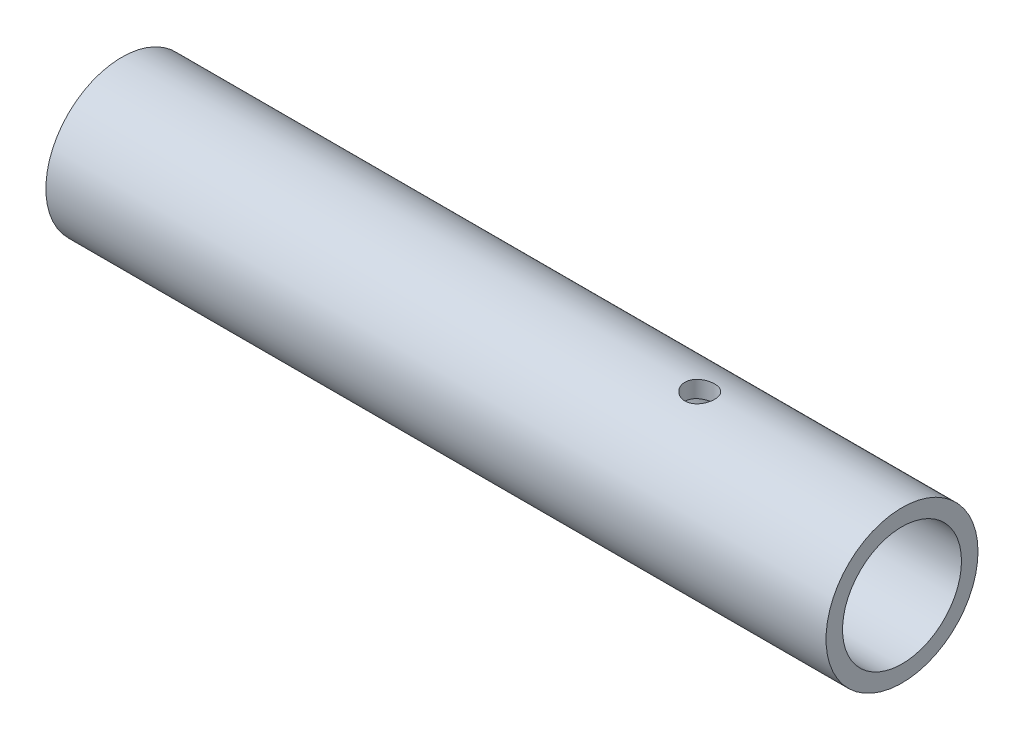
SolidWorks part; units mm, degrees
ref_plane "Front Plane" through (0, 0, 0) normal (0, 0, 1) x (1, 0, 0)
ref_plane "Top Plane" through (0, 0, 0) normal (0, 1, 0) x (1, 0, 0)
ref_plane "Right Plane" through (0, 0, 0) normal (1, 0, 0) x (0, 0, -1)
sketch "Sketch1" plane through (0, 0, 0) normal (1, 0, 0) x (0, 0, -1)
  circle A0 centre (0, 0) radius 16.7005
  circle A1 centre (0, 0) radius 13.0683
  dimension "D1" = 33.401
  dimension "D2" = 26.1366
extrude "Boss-Extrude1" add sketch "Sketch1" along normal blind 254
sketch "Sketch2" plane through (0, 0, 0) normal (0, 0, 1) x (1, 0, 0)
  line L0 (0, 0) -> (25.4, 0) construction
  line L1 (0, 16.7005) -> (0, -16.7005) construction
  line L2 (127, 16.7005) -> (127, -16.7005) construction
  line L3 (254, 16.7005) -> (0, 16.7005) construction
  line L4 (0, -16.7005) -> (254, -16.7005) construction
  line L5 (254, 0) -> (228.6, 0) construction
  circle A0 centre (25.4, 0) radius 3.2639
  circle A1 centre (228.6, 0) radius 3.2639
  dimension "D1" = 6.5278
  dimension "D2" = 25.4
extrude "Cut-Extrude1" [suppressed] cut sketch "Sketch2" against normal through all both and the other way through all
sketch "Sketch3" plane through (0, 0, 0) normal (0, 1, 0) x (1, 0, 0)
  line L0 (127, 16.7005) -> (127, -16.7005) construction
  line L1 (254, 16.7005) -> (0, 16.7005) construction
  line L2 (0, -16.7005) -> (254, -16.7005) construction
  circle A0 centre (127, 0) radius 3.2639
  dimension "D1" = 6.5278
extrude "Cut-Extrude2" cut sketch "Sketch3" against normal through all both and the other way through all
sketch "Sketch4" plane through (254, 0, 0) normal (1, 0, 0) x (0, 0, -1)
  circle A0 centre (0, 0) radius 16.7005 construction
  circle A1 centre (0, 0) radius 16.7005
extrude "Cut-Extrude4" cut sketch "Sketch4" against normal blind 82.55
